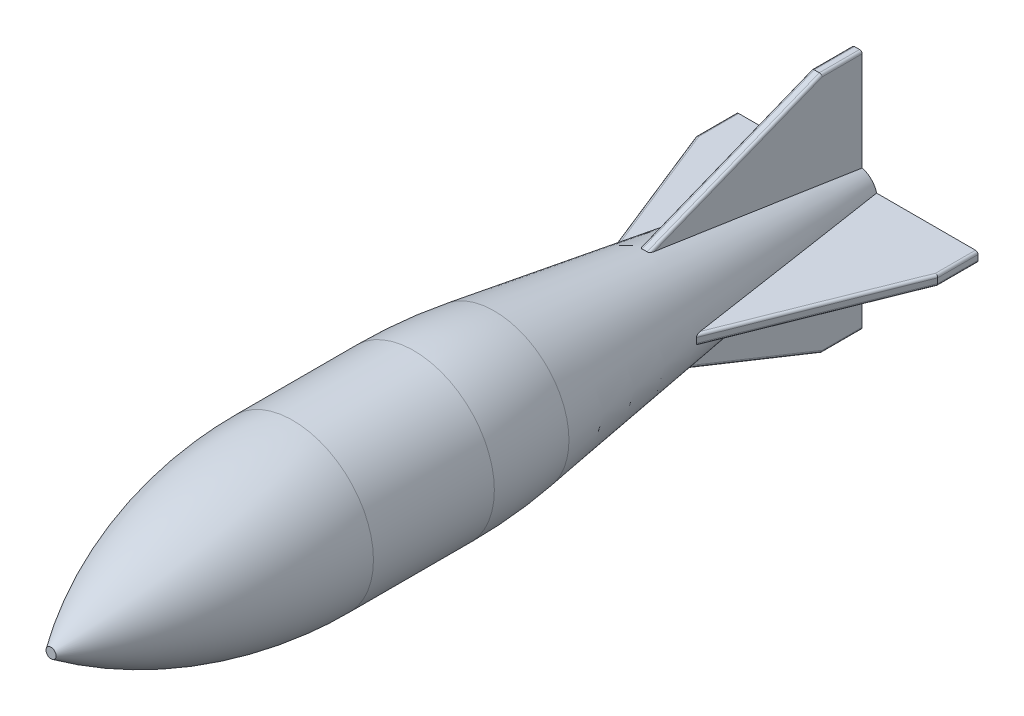
SolidWorks part; units mm, degrees
ref_plane "Front Plane" through (0, 0, 0) normal (0, 0, 1) x (1, 0, 0)
ref_plane "Top Plane" through (0, 0, 0) normal (0, 1, 0) x (1, 0, 0)
ref_plane "Right Plane" through (0, 0, 0) normal (1, 0, 0) x (0, 0, -1)
sketch "Sketch3" plane through (0, 0, 0) normal (1, 0, 0) x (0, 0, -1)
  line L0 (0, 0) -> (127, 0)
  line L1 (127, 0) -> (127, 3.175)
  line L3 (38.1, 12.7) -> (57.15, 12.7)
  line L5 (69.85, 11.7523) -> (127, 3.175)
  line L6 (0, 0) -> (0, 0.7937)
  arc A1 (57.15, 12.7) -> (69.85, 11.7523) centre (57.15, -72.8672) cw
  arc A2 (0, 0.7937) -> (38.1, 12.7) centre (38.1, -54.2131) cw
  dimension "D1" = 12.7
  dimension "D5" = 57.15
  dimension "D6" = 0.7937
  dimension "D2" = 38.1
  dimension "D3" = 3.175
  dimension "D4" = 19.05
  dimension "D7" = 127
revolve "Revolve2" add sketch "Sketch3" angle 360 about L0
sketch "Sketch5" plane through (0, 0, 0) normal (1, 0, 0) x (0, 0, -1)
  line L1 (120.65, 19.05) -> (127, 19.05)
  line L2 (120.65, 19.05) -> (88.9, 6.35)
  line L3 (127, 19.05) -> (127, 0)
  line L6 (88.9, 6.35) -> (127, 0)
  line L7 (127, -3.175) -> (127, 3.175) construction
  point P0 (0, 0)
  dimension "D1" = 19.05
  dimension "D2" = 6.35
  dimension "D3" = 6.35
  dimension "D4" = 38.1
extrude "Boss-Extrude2" add sketch "Sketch5" along normal mid plane 1.5875
fillet "Fillet2" radius 0.3969 4 edges at (-0.7937, 19.05, -123.825) (0.7937, 19.05, -123.825) (-0.7937, 13.6107, -107.0517) (0.7937, 13.6107, -107.0517)
ref_plane "Plane1" through (0, 0, -114.3) normal (0, 0, -1) x (-1, 0, 0)
sketch "Sketch6" plane through (0, 0, -114.3) normal (0, 0, -1) x (-1, 0, 0)
  circle A0 centre (0, 0) radius 6.35
  dimension "D1" = 12.7
pattern_circular "CirPattern5" count 4 over 360 about axis through (0, 0, 0) along (0, 0, 1) of "Fillet2", "Boss-Extrude2"
